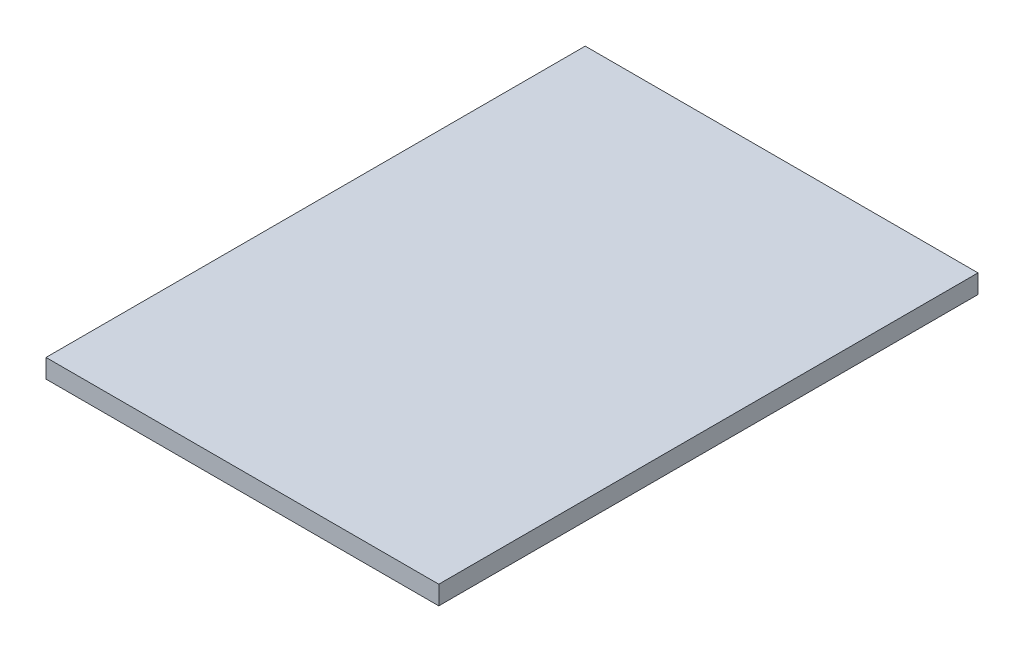
SolidWorks part; units mm, degrees
ref_plane "Front Plane" through (0, 0, 0) normal (0, 0, 1) x (1, 0, 0)
ref_plane "Top Plane" through (0, 0, 0) normal (0, 1, 0) x (1, 0, 0)
ref_plane "Right Plane" through (0, 0, 0) normal (1, 0, 0) x (0, 0, -1)
sketch "Sketch1" plane through (0, 0, 0) normal (0, 1, 0) x (1, 0, 0)
  line L1 (-66.3516, -91.0946) -> (66.3516, -91.0946)
  line L2 (-66.3516, -91.0946) -> (-66.3516, 91.0946)
  line L3 (-66.3516, 91.0946) -> (66.3516, 91.0946)
  line L4 (66.3516, -91.0946) -> (66.3516, 91.0946)
  line L5 (-66.3516, -91.0946) -> (66.3516, 91.0946) construction
  line L6 (-66.3516, 91.0946) -> (66.3516, -91.0946) construction
  point P0 (0, 0)
  point P6 (76.489, 100.9875)
  point P7 (66.3516, 91.0946)
extrude "Boss-Extrude1" add sketch "Sketch1" along normal blind 6.35
